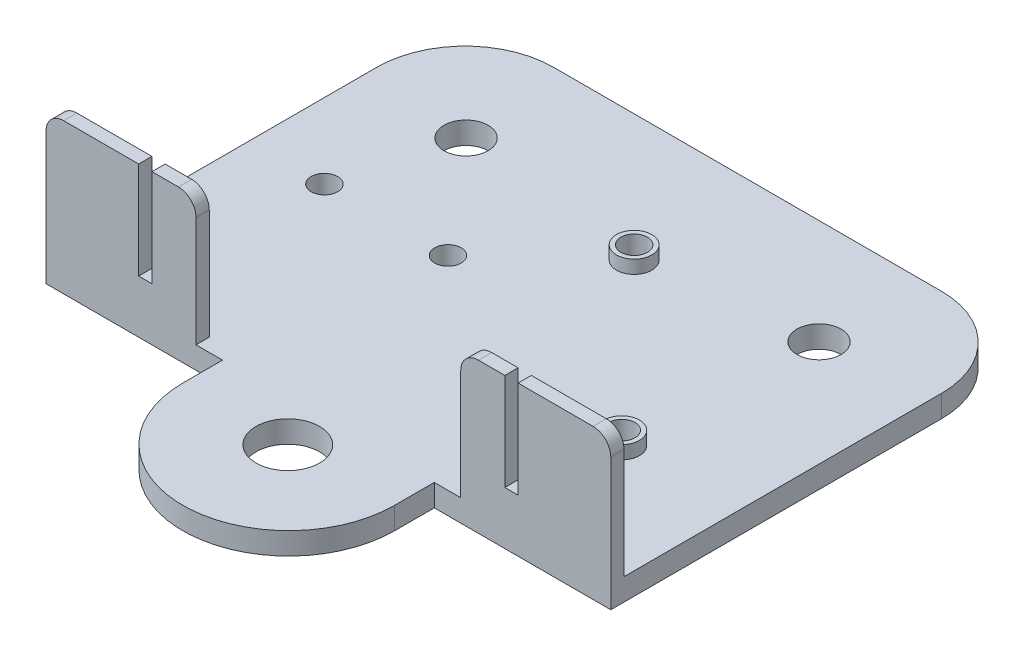
SolidWorks part; units mm, degrees
material "AISI 1020"
ref_plane "Front Plane" through (0, 0, 0) normal (0, 0, 1) x (1, 0, 0)
ref_plane "Top Plane" through (0, 0, 0) normal (0, 1, 0) x (1, 0, 0)
ref_plane "Right Plane" through (0, 0, 0) normal (1, 0, 0) x (0, 0, -1)
sketch "Sketch1" plane through (0, 0, 0) normal (0, 1, 0) x (1, 0, 0)
  line L0 (32, 0) -> (12, 0)
  line L1 (-32, 0) -> (-32, 37.5)
  line L2 (32, 0) -> (32, 37.5)
  line L3 (-22, 47.5) -> (22, 47.5)
  line L4 (-12, 0) -> (-12, -4.5)
  line L5 (12, 0) -> (12, -4.5)
  line L6 (-12, 0) -> (-32, 0)
  arc A0 (-32, 37.5) -> (-22, 47.5) centre (-22, 37.5) cw
  arc A1 (32, 37.5) -> (22, 47.5) centre (22, 37.5) ccw
  arc A2 (-12, -4.5) -> (12, -4.5) centre (0, -4.5) ccw
  circle A4 centre (0, -4.6) radius 3.6
  circle A5 centre (20, 35.6) radius 2.5
  circle A6 centre (-20, 35.6) radius 2.5
  dimension "D3" = 10
  dimension "D4" = 10
  dimension "D6" = 12
  dimension "D8" = 5
  dimension "D9" = 5
  dimension "D11" = 12
  dimension "D12" = 12
  dimension "D13" = 11.9
  dimension "D14" = 7.2
  dimension "D15" = 4.6
  dimension "D1" = 47.5
  dimension "D2" = 64
  dimension "D5" = 4.5
  dimension "D7" = 20
  dimension "D10" = 11.9
extrude "main boss" add sketch "Sketch1" along normal blind 2.5
sketch "Sketch2" plane through (0, 2.5, 0) normal (0, 1, 0) x (1, 0, 0)
  line L0 (22, 47.5) -> (-22, 47.5) construction
  line L1 (-32, 37.5) -> (-32, 0) construction
  line L2 (32, 0) -> (32, 37.5) construction
  line L3 (12, 0) -> (32, 0) construction
  circle A0 centre (1.5, 33.15) radius 2
  circle A1 centre (19, 14.25) radius 2
  dimension "D1" = 4
  dimension "D2" = 4
  dimension "D3" = 14.35
  dimension "D4" = 33.5
  dimension "D5" = 13
  dimension "D6" = 14.25
extrude "small hole extrude" add sketch "Sketch2" along normal blind 1.5
sketch "Sketch3" plane through (0, 4, 0) normal (0, 1, 0) x (1, 0, 0)
  circle A0 centre (1.5, 33.15) radius 1.5
  circle A1 centre (19, 14.25) radius 1.5
  dimension "D1" = 3
  dimension "D2" = 3
extrude "small hole" cut sketch "Sketch3" against normal through all
sketch "Sketch4" plane through (0, 0, 0) normal (0, -1, 0) x (1, 0, 0)
  line L0 (-32, -37.5) -> (-32, 0) construction
  line L2 (22, -47.5) -> (-22, -47.5) construction
  circle A0 centre (-23.5, -23.05) radius 2
  circle A1 centre (-9.5, -23.05) radius 2
  dimension "D1" = 4
  dimension "D2" = 4
  dimension "D3" = 8.5
  dimension "D4" = 14
  dimension "D5" = 24.45
extrude "long hole extrude" add sketch "Sketch4" along normal blind 4.5
sketch "Sketch5" plane through (0, -4.5, 0) normal (0, -1, 0) x (1, 0, 0)
  circle A0 centre (-23.5, -23.05) radius 1.5
  circle A1 centre (-9.5, -23.05) radius 1.5
  dimension "D1" = 3
  dimension "D2" = 3
extrude "long hole" cut sketch "Sketch5" against normal through all
sketch "Sketch6" plane through (0, 0, 0) normal (0, 0, 1) x (1, 0, 0)
  line L0 (-32, 0) -> (-32, 15)
  line L1 (-15, 0) -> (-15, 15)
  line L2 (-32, 0) -> (-12, 0) construction
  line L3 (-30, 17) -> (-21.5, 17)
  line L4 (-32, 0) -> (-15, 0)
  line L5 (-20, 17) -> (-20, 6)
  line L6 (-20, 6) -> (-21.5, 6)
  line L7 (-21.5, 6) -> (-21.5, 17)
  line L8 (-20, 17) -> (-17, 17)
  arc A0 (-32, 15) -> (-30, 17) centre (-30, 15) cw
  arc A1 (-15, 15) -> (-17, 17) centre (-17, 15) ccw
  dimension "D2" = 2
  dimension "D3" = 2
  dimension "D1" = 17
  dimension "D4" = 17
  dimension "D5" = 5
  dimension "D6" = 1.5
  dimension "D7" = 11
extrude "side boss" add sketch "Sketch6" against normal blind 1.5
mirror "Mirror1" about plane through (0, 0, 0) normal (1, 0, 0) of "side boss"
